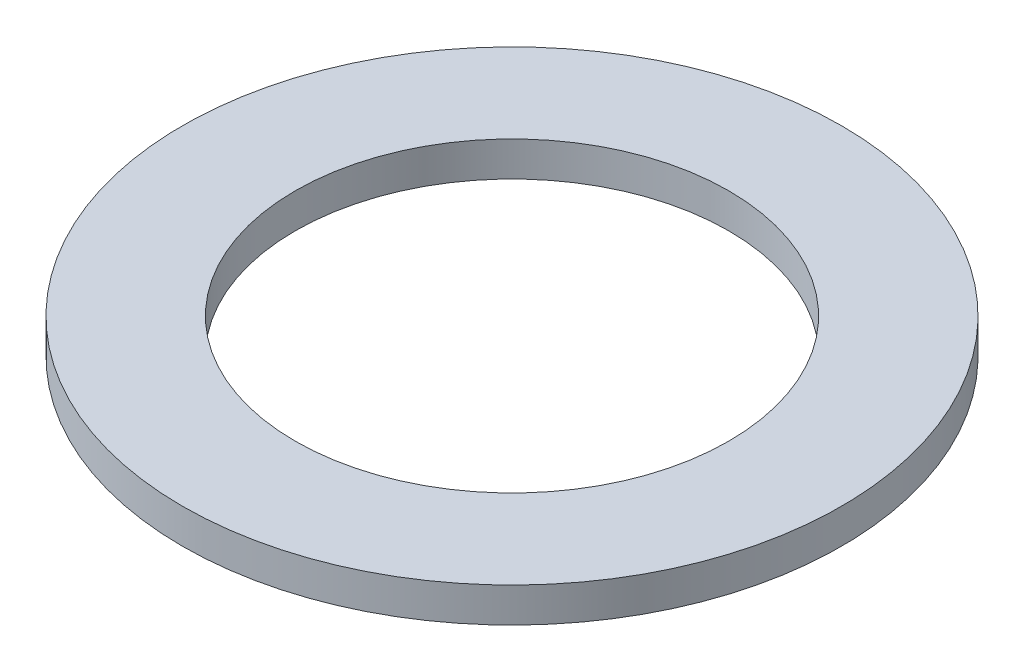
SolidWorks part; units mm, degrees
material "Delrin 2700 NC010, Low Viscosity Acetal Copolymer (SS)"
ref_plane "Front Plane" through (0, 0, 0) normal (0, 0, 1) x (1, 0, 0)
ref_plane "Top Plane" through (0, 0, 0) normal (0, 1, 0) x (1, 0, 0)
ref_plane "Right Plane" through (0, 0, 0) normal (1, 0, 0) x (0, 0, -1)
sketch "Sketch1" plane through (0, 0, 0) normal (0, 1, 0) x (1, 0, 0)
  circle A0 centre (0, 0) radius 12.5
  circle A1 centre (0, 0) radius 19
  dimension "D1" = 38
  dimension "D2" = 25
extrude "Boss-Extrude1" add sketch "Sketch1" along normal blind 2
